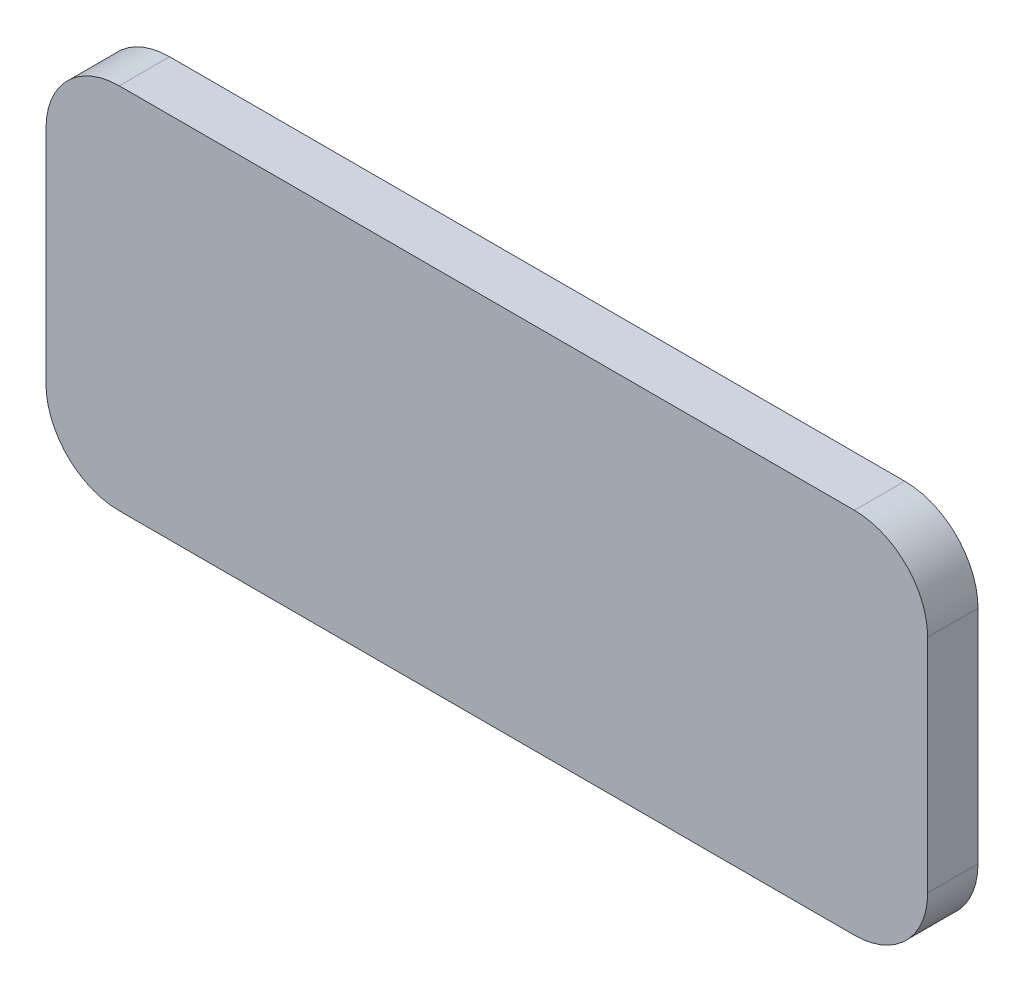
SolidWorks part; units mm, degrees
ref_plane "Front Plane" through (0, 0, 0) normal (0, 0, 1) x (1, 0, 0)
ref_plane "Top Plane" through (0, 0, 0) normal (0, 1, 0) x (1, 0, 0)
ref_plane "Right Plane" through (0, 0, 0) normal (1, 0, 0) x (0, 0, -1)
sketch "Sketch1" plane through (0, 0, 0) normal (0, 0, 1) x (1, 0, 0)
  line L1 (-43.0173, 84.2239) -> (160.9447, 84.2239)
  line L2 (-63.3373, 63.9039) -> (-63.3373, 2.4359)
  line L3 (-43.0173, -17.8841) -> (160.9447, -17.8841)
  line L4 (181.2647, 63.9039) -> (181.2647, 2.4359)
  line L5 (-27.5233, 84.2239) -> (-27.5233, -17.8841)
  line L7 (145.4507, 84.2239) -> (145.4507, -17.8841)
  arc A0 (-63.3373, 63.9039) -> (-43.0173, 84.2239) centre (-43.0173, 63.9039) cw
  arc A1 (-63.3373, 2.4359) -> (-43.0173, -17.8841) centre (-43.0173, 2.4359) ccw
  arc A2 (181.2647, 63.9039) -> (160.9447, 84.2239) centre (160.9447, 63.9039) ccw
  arc A3 (160.9447, -17.8841) -> (181.2647, 2.4359) centre (160.9447, 2.4359) ccw
  point P10 (-63.3373, 84.2239)
  point P13 (-63.3373, -17.8841)
  point P16 (181.2647, 84.2239)
  dimension "D5" = 20.32
  dimension "D6" = 20.32
  dimension "D7" = 20.32
  dimension "D8" = 20.32
  dimension "D1" = 244.602
  dimension "D2" = 102.108
  dimension "D3" = 35.814
  dimension "D4" = 35.814
extrude "Boss-Extrude1" add sketch "Sketch1" along normal blind 13.97 contours L7 L1 L5 L3 | L2 A1 L3 L5 L1 A0 | L3 A3 L4 A2 L1 L7
sketch "Sketch2" plane through (0, 0, 0) normal (0, 0, -1) x (-1, 0, 0)
  line L0 (-145.4507, 84.2239) -> (-145.4507, -17.8841)
  line L1 (43.0173, 84.2239) -> (-160.9447, 84.2239) construction
  line L2 (43.0173, -17.8841) -> (-160.9447, -17.8841) construction
  line L3 (-181.2647, 63.9039) -> (-181.2647, 2.4359) construction
  line L5 (-156.6365, 76.06) -> (-148.8243, 76.06)
  line L6 (-156.6365, 76.06) -> (-156.6365, 73.6521)
  line L7 (-156.6365, 73.6521) -> (-148.8243, 73.6521)
  line L8 (-148.8243, 76.06) -> (-148.8243, 73.6521)
  circle A0 centre (-163.4847, 58.8239) radius 7.4676
  circle A1 centre (-170.3371, 26.676) radius 3.015
  circle A2 centre (-163.2212, 32.8237) radius 3.015
  circle A3 centre (-156.7324, 26.2052) radius 3.015
  circle A4 centre (-163.7215, 19.9736) radius 3.015
  point P16 (0, 0)
  point P23 (0, 0)
  dimension "D2" = 17.78
  dimension "D1" = 35.814
  dimension "D3" = 25.4
extrude "Boss-Extrude3" add sketch "Sketch2" along normal blind 3.048 contours A3 | A2 | A4 | A1 | A0 | L6 L7 L8 L5
sketch "Sketch3" plane through (0, 0, 0) normal (0, 0, -1) x (-1, 0, 0)
  line L0 (27.7773, 84.2239) -> (27.7773, -17.8841)
  line L1 (43.0173, 84.2239) -> (-160.9447, 84.2239) construction
  line L2 (43.0173, -17.8841) -> (-160.9447, -17.8841) construction
  line L3 (63.3373, 63.9039) -> (63.3373, 2.4359) construction
  line L4 (35.9334, 76.3914) -> (35.9334, 78.9314)
  line L6 (33.5703, 76.3914) -> (33.5703, 73.9836)
  line L8 (41.1903, 76.3914) -> (41.1903, 73.9836)
  line L9 (35.9334, 78.9314) -> (38.4734, 78.9314)
  line L10 (38.4734, 76.3914) -> (38.4734, 78.9314)
  line L11 (38.4734, 73.9836) -> (38.4734, 71.4436)
  line L12 (38.4734, 71.4436) -> (35.9334, 71.4436)
  line L13 (35.9334, 71.4436) -> (35.9334, 73.9836)
  line L14 (41.1903, 73.9836) -> (38.4734, 73.9836)
  line L15 (33.5703, 73.9836) -> (35.9334, 73.9836)
  line L16 (33.5703, 76.3914) -> (35.9334, 76.3914)
  line L17 (38.4734, 76.3914) -> (41.1903, 76.3914)
  circle A0 centre (45.4875, 28.5164) radius 7.4676
  circle A1 centre (38.3418, 59.8184) radius 3.015
  circle A2 centre (45.4577, 65.9661) radius 3.015
  circle A3 centre (51.9466, 59.3476) radius 3.015
  circle A4 centre (44.9575, 53.1161) radius 3.015
  dimension "D1" = 35.56
extrude "Boss-Extrude5" add sketch "Sketch3" along normal blind 3.048 contours A0 | A4 | A1 | A2 | A3 | L17 L10 L9 L4 L16 L6 L15 L13 L12 L11 L14 L8
